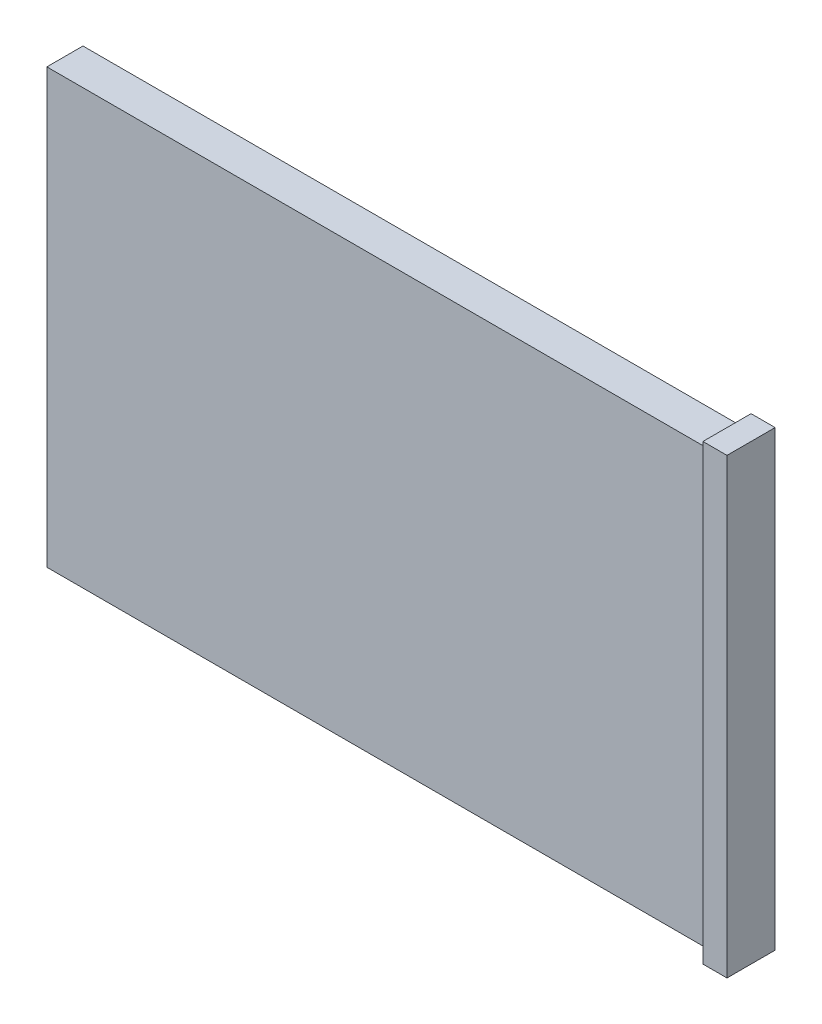
SolidWorks part; units mm, degrees
ref_plane "Front Plane" through (0, 0, 0) normal (0, 0, 1) x (1, 0, 0)
ref_plane "Top Plane" through (0, 0, 0) normal (0, 1, 0) x (1, 0, 0)
ref_plane "Right Plane" through (0, 0, 0) normal (1, 0, 0) x (0, 0, -1)
sketch "Эскиз1" plane through (0, 0, 0) normal (0, 0, 1) x (1, 0, 0)
  line L1 (13.75, -9) -> (-13.75, -9)
  line L2 (13.75, -9) -> (13.75, 9)
  line L3 (13.75, 9) -> (-13.75, 9)
  line L4 (-13.75, -9) -> (-13.75, 9)
  line L5 (13.75, -9) -> (-13.75, 9) construction
  line L6 (13.75, 9) -> (-13.75, -9) construction
  point P0 (0, 0)
  dimension "D1" = 18
  dimension "D2" = 27.5
extrude "Бобышка-Вытянуть1" add sketch "Эскиз1" along normal blind 1.5
sketch "Эскиз2" plane through (13.75, 0, 0) normal (1, 0, 0) x (0, 0, -1)
  line L0 (0, 0) -> (-1.5, 0) construction
  line L1 (0, -9) -> (0, 9) construction
  line L2 (-1.5, -9) -> (-1.5, 9) construction
  line L4 (0.25, -9.4) -> (-1.75, -9.4)
  line L5 (0.25, -9.4) -> (0.25, 9.4)
  line L6 (0.25, 9.4) -> (-1.75, 9.4)
  line L7 (-1.75, -9.4) -> (-1.75, 9.4)
  line L8 (0.25, -9.4) -> (-1.75, 9.4) construction
  line L9 (0.25, 9.4) -> (-1.75, -9.4) construction
  point P6 (-0.75, 0)
  dimension "D1" = 18.8
  dimension "D2" = 2
extrude "Бобышка-Вытянуть2" add sketch "Эскиз2" along normal blind 1
